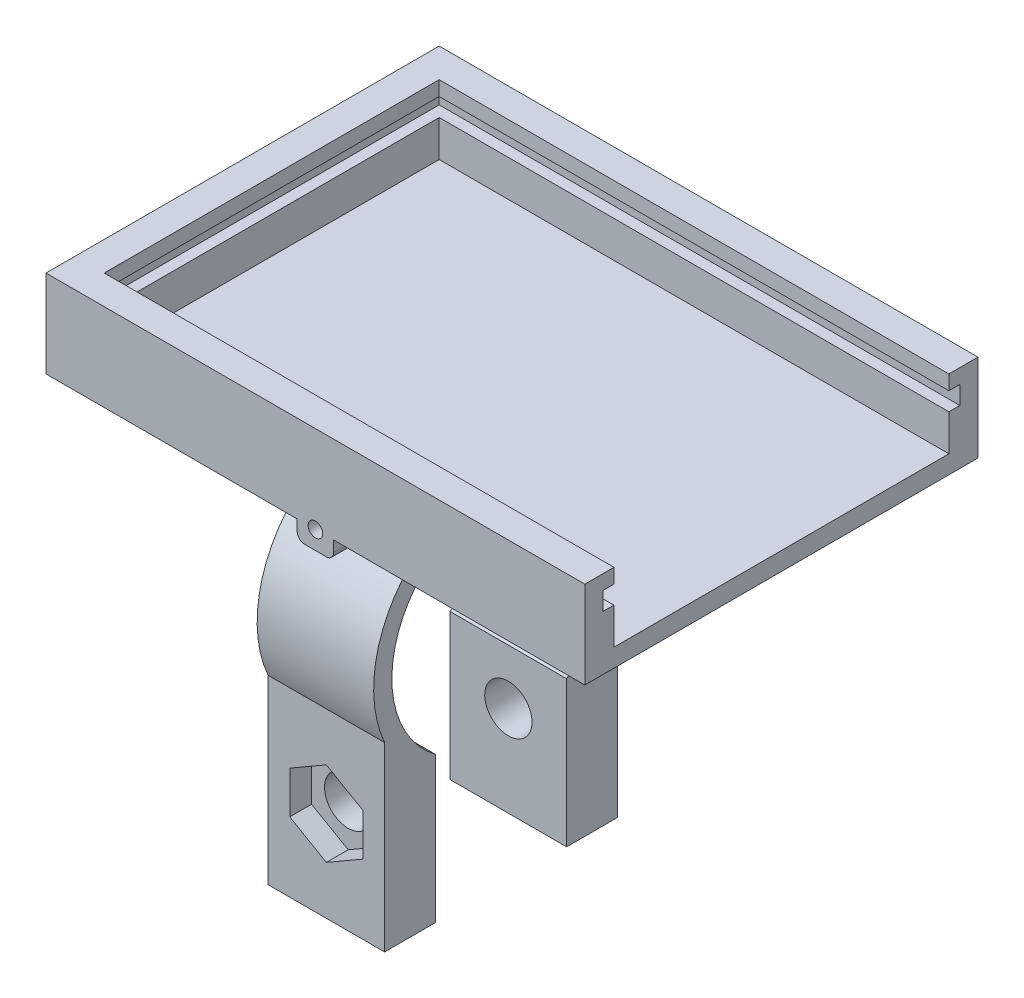
SolidWorks part; units mm, degrees
ref_plane "Alzado" through (0, 0, 0) normal (0, 0, 1) x (1, 0, 0)
ref_plane "Planta" through (0, 0, 0) normal (0, 1, 0) x (1, 0, 0)
ref_plane "Vista lateral" through (0, 0, 0) normal (1, 0, 0) x (0, 0, -1)
sketch "Croquis1" plane through (0, 0, 0) normal (0, 1, 0) x (1, 0, 0)
  line L1 (-37, 27) -> (37, 27)
  line L2 (-37, 27) -> (-37, -27)
  line L3 (-37, -27) -> (37, -27)
  line L4 (37, 27) -> (37, -27)
  line L5 (-37, 27) -> (37, -27) construction
  line L6 (-37, -27) -> (37, 27) construction
  point P0 (0, 0)
  dimension "D1" = 74
  dimension "D2" = 54
extrude "Saliente-Extruir1" add sketch "Croquis1" along normal blind 2.5
sketch "Croquis2" plane through (0, 2.5, 0) normal (0, 1, 0) x (1, 0, 0)
  line L0 (34.5, 24.5) -> (37, 24.5)
  line L1 (-37, 27) -> (37, 27)
  line L2 (-37, 27) -> (-37, -27)
  line L3 (-37, -27) -> (37, -27)
  line L4 (37, 27) -> (37, -27)
  line L5 (-37, 27) -> (37, -27) construction
  line L6 (-37, -27) -> (37, 27) construction
  line L7 (-34.5, 24.5) -> (34.5, 24.5)
  line L8 (-34.5, 24.5) -> (-34.5, -24.5)
  line L9 (-34.5, -24.5) -> (34.5, -24.5)
  line L10 (34.5, 24.5) -> (34.5, -24.5) construction
  line L11 (-34.5, 24.5) -> (34.5, -24.5) construction
  line L12 (-34.5, -24.5) -> (34.5, 24.5) construction
  line L13 (34.5, -24.5) -> (37, -24.5)
  point P0 (0, 0)
  point P5 (0, 0)
  line M10 (37, -27) -> (37, 27)
  line M11 (37, 27) -> (-37, 27)
  line M12 (-37, 27) -> (-37, -27)
  line M13 (-37, -27) -> (37, -27)
  dimension "D1" = 69
  dimension "D2" = 49
extrude "Saliente-Extruir2" add sketch "Croquis2" along normal blind 2.5 contours L13 L9 L8 L7 L0 M10 M11 M12 M13
sketch "Croquis3" plane through (0, 5, 0) normal (0, 1, 0) x (1, 0, 0)
  line L0 (-37, -27) -> (37, -27) construction
  line L1 (-37, 27) -> (37, 27)
  line L2 (-37, 27) -> (-37, -27)
  line L3 (-37, -27) -> (37, -27)
  line L4 (37, 27) -> (37, -27)
  line L5 (-37, 27) -> (37, -27) construction
  line L6 (-37, -27) -> (37, 27) construction
  line L7 (33, 23) -> (37, 23)
  line L8 (-33, 23) -> (33, 23)
  line L9 (-33, 23) -> (-33, -23)
  line L10 (-33, -23) -> (33, -23)
  line L11 (33, 23) -> (33, -23) construction
  line L12 (-33, 23) -> (33, -23) construction
  line L13 (-33, -23) -> (33, 23) construction
  line L14 (33, -23) -> (37, -23)
  point P0 (0, 0)
  point P8 (0, 0)
  line M9 (37, -24.5) -> (-34.5, -24.5)
  line M10 (-34.5, -24.5) -> (-34.5, 24.5)
  line M11 (-34.5, 24.5) -> (37, 24.5)
  line M12 (37, 24.5) -> (37, 27)
  line M13 (37, 27) -> (-37, 27)
  line M14 (-37, 27) -> (-37, -27)
  line M15 (-37, -27) -> (37, -27)
  line M16 (37, -27) -> (37, -24.5)
  dimension "D1" = 66
  dimension "D2" = 46
  dimension "D3" = 74
extrude "Saliente-Extruir3" add sketch "Croquis3" along normal blind 2 contours L14 L10 L9 L8 L7 L4 M11 M10 M9 | M16 M9 M10 M11 M12 M13 M14 M15
sketch "Croquis4" plane through (0, 0, 0) normal (0, -1, 0) x (1, 0, 0)
  line L1 (-37, 27) -> (37, 27)
  line L2 (-37, 27) -> (-37, -27)
  line L3 (-37, -27) -> (37, -27)
  line L4 (37, 27) -> (37, -27)
  line L5 (-37, 27) -> (37, -27) construction
  line L6 (-37, -27) -> (37, 27) construction
  point P0 (0, 0)
extrude "Saliente-Extruir4" add sketch "Croquis4" along normal blind 5
sketch "Croquis5" plane through (0, 2.5, 0) normal (0, 1, 0) x (1, 0, 0)
  line L0 (-33, 23) -> (37, 23)
  line L1 (37, 23) -> (37, -23)
  line L2 (37, -23) -> (-33, -23)
  line L3 (-33, 23) -> (-33, -23) construction
  line L4 (-33, -23) -> (-33, 23)
extrude "Cortar-Extruir1" cut sketch "Croquis5" against normal blind 5
sketch "Croquis6" plane through (0, -5, 0) normal (0, -1, 0) x (1, 0, 0)
  line L0 (0, 0) -> (-37, 0) construction
  line L1 (-37, 27) -> (-37, -27) construction
  line L4 (-37, -27) -> (37, -27) construction
  line L5 (2.5, 27) -> (-2.5, 27)
  line L6 (2.5, 27) -> (2.5, -27)
  line L7 (2.5, -27) -> (-2.5, -27)
  line L8 (-2.5, 27) -> (-2.5, -27)
  line L9 (2.5, 27) -> (-2.5, -27) construction
  line L10 (2.5, -27) -> (-2.5, 27) construction
  dimension "D1" = 54
extrude "Saliente-Extruir5" add sketch "Croquis6" along normal mid plane 5
fillet "Redondeo1" radius 1 2 edges at (-2.5, -7.5, 0) (2.5, -7.5, 0)
sketch "Croquis7" plane through (0, 0, 27) normal (0, 0, 1) x (1, 0, 0)
  line L0 (1.5, -7.5) -> (-1.5, -7.5) construction
  line L1 (0, 0) -> (0, -5) construction
  circle A0 centre (0, -5) radius 1
  dimension "D1" = 2
  dimension "D2" = 2.5
extrude "Cortar-Extruir2" cut sketch "Croquis7" against normal blind 100
sketch "Croquis9" plane through (0, 0, 0) normal (1, 0, 0) x (0, 0, -1)
  line L0 (0, 0) -> (0, -5) construction
  line L2 (-27, -5) -> (-27, -33.3845) construction
  line L3 (-9.5, -20) -> (-9.5, -42.0255) construction
  line L4 (-18.5, -32) -> (-18.5, -52)
  line L5 (-25.5, -52) -> (-18.5, -52)
  line L6 (-25.5, -52) -> (-25.5, -27.0887)
  line L7 (6.5, -52) -> (-0.5, -52)
  line L8 (6.5, -52) -> (6.5, -27.0887)
  line L9 (-0.5, -32) -> (-0.5, -52)
  line L10 (-27, -5) -> (27, -5) construction
  line L11 (0, -2.5) -> (-27, -2.5) construction
  line L12 (-27, 7) -> (-27, -5) construction
  arc A1 (-0.5, -32) -> (-18.5, -32) centre (-9.5, -20) ccw
  arc A2 (6.5, -27.0887) -> (-25.5, -27.0887) centre (-9.5, -20) ccw
  dimension "D1" = 17.5
  dimension "D2" = 30
  dimension "D3" = 7
  dimension "D4" = 20
  dimension "D5" = 9
extrude "Saliente-Extruir9" add sketch "Croquis9" along normal mid plane 16 separate body
sketch "Croquis10" plane through (8, 0, 0) normal (1, 0, 0) x (0, 0, -1)
  line L0 (-24.5, -20) -> (5.5, -20) construction
  arc A0 (-0.5, -32) -> (-18.5, -32) centre (-9.5, -20) ccw construction
  circle A1 centre (-9.5, -20) radius 15
  dimension "D1" = 30
extrude "Cortar-Extruir3" cut sketch "Croquis10" against normal blind 16
sketch "Croquis11" plane through (0, 0, 25.5) normal (0, 0, 1) x (1, 0, 0)
  line L0 (0, -39.5444) -> (22.7854, -39.5444) construction
  line L1 (0, -45.3444) -> (5.0229, -42.4444)
  line L2 (5.0229, -42.4444) -> (5.0229, -36.6444)
  line L3 (5.0229, -36.6444) -> (0, -33.7444)
  line L4 (0, -33.7444) -> (-5.0229, -36.6444)
  line L5 (-5.0229, -36.6444) -> (-5.0229, -42.4444)
  line L6 (-5.0229, -42.4444) -> (0, -45.3444)
  line L7 (0, -52) -> (0, -27.0887) construction
  line L8 (8, -52) -> (-8, -52) construction
  line L9 (8, -27.0887) -> (-8, -27.0887) construction
  line L10 (-8, -27.0887) -> (-8, -52) construction
  circle A0 centre (0, -39.5444) radius 5.0229 construction
  point P18 (0, 0)
  point P19 (0, -39.5444)
  dimension "D1" = 5.8
  dimension "D6" = 24.9113
extrude "Cortar-Extruir4" cut sketch "Croquis11" against normal blind 3
sketch "Croquis12" plane through (0, 0, 22.5) normal (0, 0, 1) x (1, 0, 0)
  line L0 (0, -33.7444) -> (0, -45.3444) construction
  circle A0 centre (0, -39.5444) radius 3.25
  dimension "D1" = 6.5
extrude "Cortar-Extruir5" cut sketch "Croquis12" against normal blind 100
